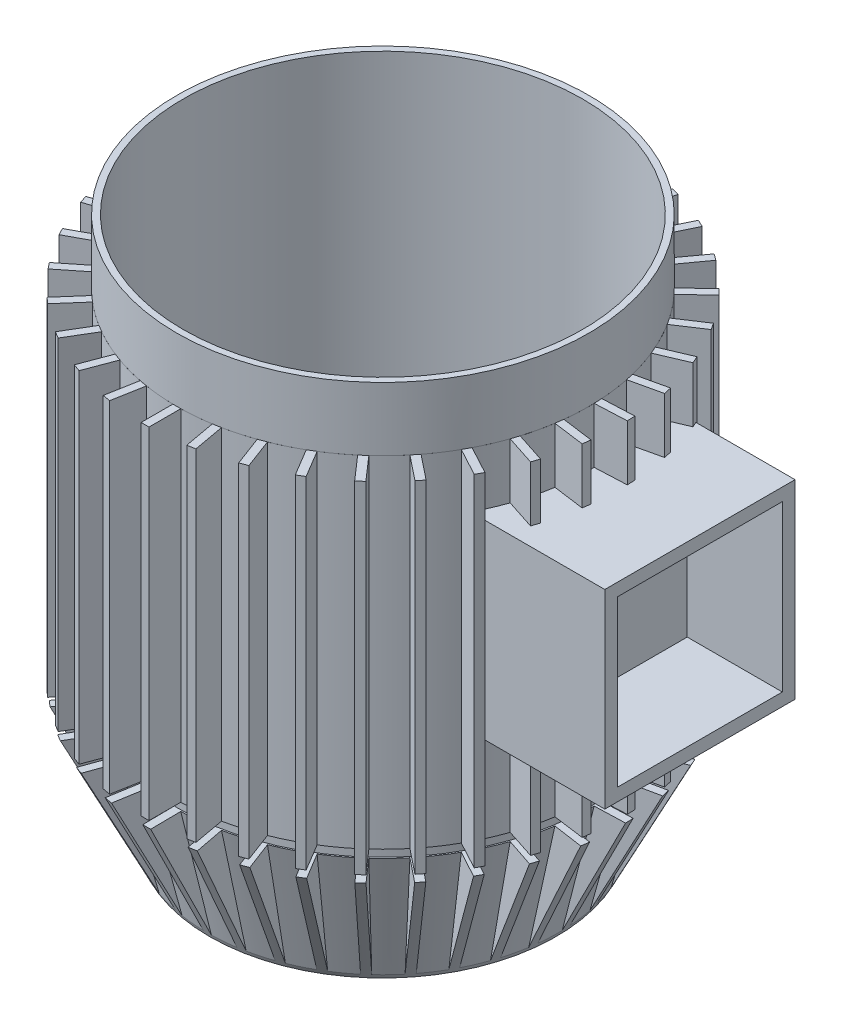
SolidWorks part; units mm, degrees
ref_plane "Front Plane" through (0, 0, 0) normal (0, 0, 1) x (1, 0, 0)
ref_plane "Top Plane" through (0, 0, 0) normal (0, 1, 0) x (1, 0, 0)
ref_plane "Right Plane" through (0, 0, 0) normal (1, 0, 0) x (0, 0, -1)
sketch "Sketch1" plane through (0, 0, 0) normal (0, 1, 0) x (1, 0, 0)
  circle A0 centre (0, 0) radius 65
  dimension "D1" = 130
extrude "Boss-Extrude1" add sketch "Sketch1" against normal blind 170
chamfer "Chamfer1" distance 10 distance2 40 1 edges at (0, -170, 65)
shell "Shell1" thickness 2
ref_plane "Plane1" through (0, 0, 75) normal (0, 0, 1) x (1, 0, 0)
sketch "Sketch2" plane through (0, 0, 75) normal (0, 0, 1) x (1, 0, 0)
  line L0 (65, 0) -> (-65, 0) construction
  line L1 (-1.25, 0) -> (1.25, 0)
  line L2 (-1.25, 0) -> (-1.25, -170)
  line L3 (-1.25, -170) -> (1.25, -170)
  line L4 (1.25, 0) -> (1.25, -170)
  line L5 (-55, -170) -> (55, -170) construction
  line L6 (0, 0) -> (0, -170) construction
  dimension "D1" = 2.5
extrude "Boss-Extrude2" add sketch "Sketch2" against normal up to next
pattern_circular "CirPattern1" count 35 over 360 about axis through (0, 0, 0) along (0, 1, 0) of "Boss-Extrude2"
sketch "Sketch3" plane through (0, 0, 0) normal (0, 0, 1) x (1, 0, 0)
  line L0 (54.656, -170) -> (74.489, -130.1194)
  line L1 (74.489, -170) -> (74.489, 0) construction
  line L2 (54.656, -170) -> (90.451, -179.2784)
  line L3 (90.451, -179.2784) -> (90.451, -127.5)
  line L4 (90.451, -127.5) -> (64.5676, -127.5)
  line L5 (64.5676, 0) -> (64.5676, -130) construction
  line L6 (64.5676, -127.5) -> (64.5676, -130)
  line L7 (64.5676, -130) -> (74.489, -130.1194)
  line L8 (0, 0) -> (0, -216.905) construction
  line L9 (63, 0) -> (-63, 0) construction
  dimension "D1" = 2.5
revolve "Cut-Revolve1" cut sketch "Sketch3" angle 360 about L8
sketch "Sketch4" plane through (0, -170, 0) normal (0, -1, 0) x (1, 0, 0)
  circle A0 centre (0, 0) radius 10
  dimension "D1" = 20
extrude "Cut-Extrude1" cut sketch "Sketch4" against normal through all
ref_plane "Plane2" through (100, 0, 0) normal (1, 0, 0) x (0, 0, -1)
sketch "Sketch5" plane through (100, 0, 0) normal (1, 0, 0) x (0, 0, -1)
  line L0 (0, 0) -> (0, -176.5661) construction
  line L1 (-18.8936, -127.5) -> (-9.9622, -127.5) construction
  line L2 (-30, -37.5) -> (30, -37.5)
  line L3 (-30, -37.5) -> (-30, -97.5)
  line L4 (-30, -97.5) -> (30, -97.5)
  line L5 (30, -37.5) -> (30, -97.5)
  dimension "D1" = 60
  dimension "D2" = 60
  dimension "D3" = 30
extrude "Boss-Extrude3" add sketch "Sketch5" against normal up to next
sketch "Sketch6" plane through (100, 0, 0) normal (1, 0, 0) x (0, 0, -1)
  line L16 (-26, -41.5) -> (-26, -93.5)
  line L17 (-26, -93.5) -> (26, -93.5)
  line L18 (26, -93.5) -> (26, -41.5)
  line L19 (26, -41.5) -> (-26, -41.5)
  line L20 (-26, -41.5) -> (-26, -93.5)
  line L21 (-26, -93.5) -> (26, -93.5)
  line L22 (26, -93.5) -> (26, -41.5)
  line L23 (26, -41.5) -> (-26, -41.5)
  dimension "D1" = 4
extrude "Cut-Extrude2" cut sketch "Sketch6" against normal blind 30
sketch "Sketch7" plane through (0, 0, 0) normal (1, 0, 0) x (0, 0, -1)
  line L0 (-64.988, -127.5) -> (-64.988, 0) construction
  line L1 (-80.5547, 0) -> (-64.988, 0)
  line L2 (-80.5547, 0) -> (-80.5547, -20)
  line L3 (-80.5547, -20) -> (-64.988, -20)
  line L4 (-64.988, 0) -> (-64.988, -20)
  line L5 (0, 35.7548) -> (0, -66.4022) construction
  dimension "D1" = 20
revolve "Cut-Revolve2" cut sketch "Sketch7" angle 360 about L5
